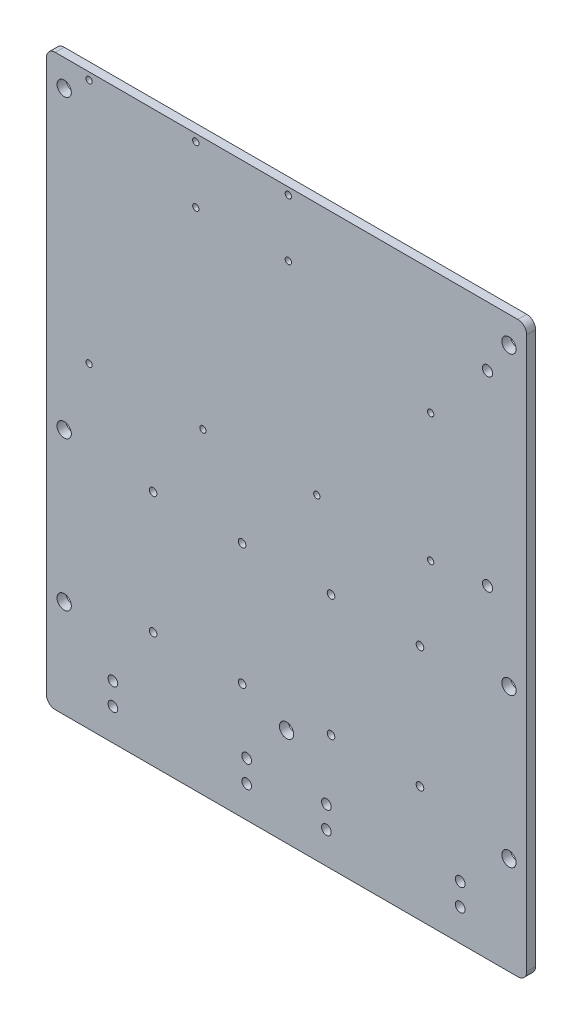
SolidWorks part; units mm, degrees
material "6061-T6 (SS)"
ref_plane "Front" through (0, 0, 0) normal (0, 0, 1) x (1, 0, 0)
ref_plane "Top" through (0, 0, 0) normal (0, 1, 0) x (1, 0, 0)
ref_plane "Right" through (0, 0, 0) normal (1, 0, 0) x (0, 0, -1)
sketch "Sketch1" plane through (0, 0, 0) normal (0, 0, 1) x (1, 0, 0)
  line L1 (-85.725, 101.6) -> (85.725, 101.6)
  line L2 (-85.725, 101.6) -> (-85.725, -101.6)
  line L3 (-85.725, -101.6) -> (85.725, -101.6)
  line L4 (85.725, 101.6) -> (85.725, -101.6)
  line L5 (-85.725, 101.6) -> (85.725, -101.6) construction
  line L6 (-85.725, -101.6) -> (85.725, 101.6) construction
  point P0 (0, 0)
  dimension "D1" = 171.45
  dimension "D2" = 203.2
extrude "Boss-Extrude1" add sketch "Sketch1" along normal blind 3.175
hole_wizard "#10 Clearance Hole1" positions "Sketch2" profile "Sketch3" hole size "#10" standard "ANSI Inch" end condition through all
sketch "Sketch2" plane through (0, 0, 3.175) normal (0, 0, 1) x (1, 0, 0)
  point P0 (-79.375, 92.075)
  point P2 (79.375, 92.075)
  point P4 (79.375, -66.675)
  point P6 (-79.375, -66.675)
  point P8 (-79.375, -13.462)
  point P10 (79.375, -13.462)
  point P37 (0, -66.675)
sketch "Sketch3" plane through (-79.375, 92.075, 3.175) normal (1, 0, 0) x (0, -1, 0)
  line L0 (0, 0) -> (0, 3.175)
  line L1 (0, 3.175) -> (2.5527, 3.175)
  line L2 (2.5527, 3.175) -> (2.5527, 0)
  line L3 (2.5527, 0) -> (0, 0)
  line L4 (0, -6.35) -> (0, 107.95) construction
  dimension "Thru Hole Dia." = 5.1054
  dimension "Thru Hole Depth" = 3.175
hole_wizard "#6-32 Tapped Hole1" positions "Sketch4" profile "Sketch5" tap size "#6-32" standard "ANSI Inch" end condition through all
sketch "Sketch4" plane through (0, 0, 3.175) normal (0, 0, 1) x (1, 0, 0)
  point P0 (-47.625, -60.2)
  point P2 (-47.625, -16.8)
sketch "Sketch5" plane through (-47.625, -60.2, 3.175) normal (1, 0, 0) x (0, -1, 0)
  line L0 (0, 0) -> (0, 3.175)
  line L1 (0, 3.175) -> (1.3525, 3.175)
  line L2 (1.3525, 3.175) -> (1.3525, 0)
  line L3 (1.3525, 0) -> (0, 0)
  line L4 (0, -6.35) -> (0, 107.95) construction
  dimension "Thru Tap Drill Dia." = 2.7051
  dimension "Thru Tap Drill Depth" = 3.175
cosmetic thread "Hole Thread1" parameters "D2"=3.5052
cosmetic thread "Hole Thread2" parameters "D2"=3.5052
pattern_linear "LPattern1" count 4 spacing 31.75 along (1, 0, 0) of "#6-32 Tapped Hole1"
cosmetic thread "Hole Thread3" parameters "D2"=3.5052
cosmetic thread "Hole Thread4" parameters "D2"=3.5052
cosmetic thread "Hole Thread5" parameters "D2"=3.5052
cosmetic thread "Hole Thread6" parameters "D2"=3.5052
cosmetic thread "Hole Thread7" parameters "D2"=3.5052
cosmetic thread "Hole Thread8" parameters "D2"=3.5052
hole_wizard "#8-32 Tapped Hole1" positions "Sketch6" profile "Sketch7" tap size "#8-32" standard "ANSI Inch" end condition through all
sketch "Sketch6" plane through (0, 0, 3.175) normal (0, 0, 1) x (1, 0, 0)
  point P0 (-61.976, -82.423)
  point P2 (-61.976, -90.297)
  point P4 (-14.224, -82.423)
  point P6 (-14.224, -90.297)
sketch "Sketch7" plane through (-61.976, -82.423, 3.175) normal (1, 0, 0) x (0, -1, 0)
  line L0 (0, 0) -> (0, 3.175)
  line L1 (0, 3.175) -> (1.7272, 3.175)
  line L2 (1.7272, 3.175) -> (1.7272, 0)
  line L3 (1.7272, 0) -> (0, 0)
  line L4 (0, -6.35) -> (0, 107.95) construction
  dimension "Thru Tap Drill Dia." = 3.4544
  dimension "Thru Tap Drill Depth" = 3.175
cosmetic thread "Hole Thread9" parameters "D2"=4.1656
cosmetic thread "Hole Thread10" parameters "D2"=4.1656
cosmetic thread "Hole Thread11" parameters "D2"=4.1656
cosmetic thread "Hole Thread12" parameters "D2"=4.1656
mirror "Mirror1" about plane through (0, 0, 0) normal (1, 0, 0) of "#8-32 Tapped Hole1"
cosmetic thread "Hole Thread13" parameters "D2"=4.1656
cosmetic thread "Hole Thread14" parameters "D2"=4.1656
cosmetic thread "Hole Thread15" parameters "D2"=4.1656
cosmetic thread "Hole Thread16" parameters "D2"=4.1656
hole_wizard "M3 Clearance Hole1" positions "Sketch8" profile "Sketch9" hole size "M3" standard "ANSI Metric" end condition through all
sketch "Sketch8" plane through (0, 0, 0) normal (0, 0, -1) x (-1, 0, 0)
  point P0 (-71.725, 80.3338)
  point P2 (-71.725, 13.8338)
sketch "Sketch9" plane through (71.725, 80.3338, 0) normal (1, 0, 0) x (0, 1, 0)
  line L0 (0, 0) -> (0, 3.175)
  line L1 (0, 3.175) -> (1.8, 3.175)
  line L2 (1.8, 3.175) -> (1.8, 0)
  line L3 (1.8, 0) -> (0, 0)
  line L4 (0, -6.35) -> (0, 107.95) construction
  dimension "Thru Hole Dia." = 3.6
  dimension "Thru Hole Depth" = 3.175
fillet "Fillet1" radius 3.175 4 edges at (-85.725, -101.6, 1.5875) (-85.725, 101.6, 1.5875) (85.725, 101.6, 1.5875) (85.725, -101.6, 1.5875)
hole_wizard "#4-40 Tapped Hole1" positions "Sketch10" profile "Sketch11" tap size "#4-40" standard "ANSI Inch" end condition through all
sketch "Sketch10" plane through (0, 0, 3.175) normal (0, 0, 1) x (1, 0, 0)
  point P0 (-70.485, 99.06)
  point P2 (-32.385, 78.74)
  point P4 (-32.385, 99.06)
  point P8 (0.635, 99.06)
  point P10 (0.635, 78.74)
  point P12 (-70.485, 11.43)
  point P14 (-29.845, 11.43)
  point P16 (10.795, 11.43)
  point P18 (51.435, 11.43)
  point P20 (51.435, 57.15)
  point P51 (0, 0)
  point P54 (0, 0)
  point P57 (0, 0)
  point P60 (0, 0)
  point P63 (0, 0)
  point P66 (0, 0)
  point P67 (0, 0)
  point P70 (0, 0)
  point P73 (0, 0)
  point P76 (0, 0)
  point P79 (0, 0)
sketch "Sketch11" plane through (-70.485, 99.06, 3.175) normal (1, 0, 0) x (0, -1, 0)
  line L0 (0, 0) -> (0, 3.175)
  line L1 (0, 3.175) -> (1.1303, 3.175)
  line L2 (1.1303, 3.175) -> (1.1303, 0)
  line L3 (1.1303, 0) -> (0, 0)
  line L4 (0, -6.35) -> (0, 107.95) construction
  dimension "Thru Tap Drill Dia." = 2.2606
  dimension "Thru Tap Drill Depth" = 3.175
cosmetic thread "Hole Thread17" parameters "D2"=2.8448
cosmetic thread "Hole Thread18" parameters "D2"=2.8448
cosmetic thread "Hole Thread19" parameters "D2"=2.8448
cosmetic thread "Hole Thread20" parameters "D2"=2.8448
cosmetic thread "Hole Thread21" parameters "D2"=2.8448
cosmetic thread "Hole Thread22" parameters "D2"=2.8448
cosmetic thread "Hole Thread23" parameters "D2"=2.8448
cosmetic thread "Hole Thread25" parameters "D2"=2.8448
cosmetic thread "Hole Thread26" parameters "D2"=2.8448
cosmetic thread "Hole Thread27" parameters "D2"=2.8448
